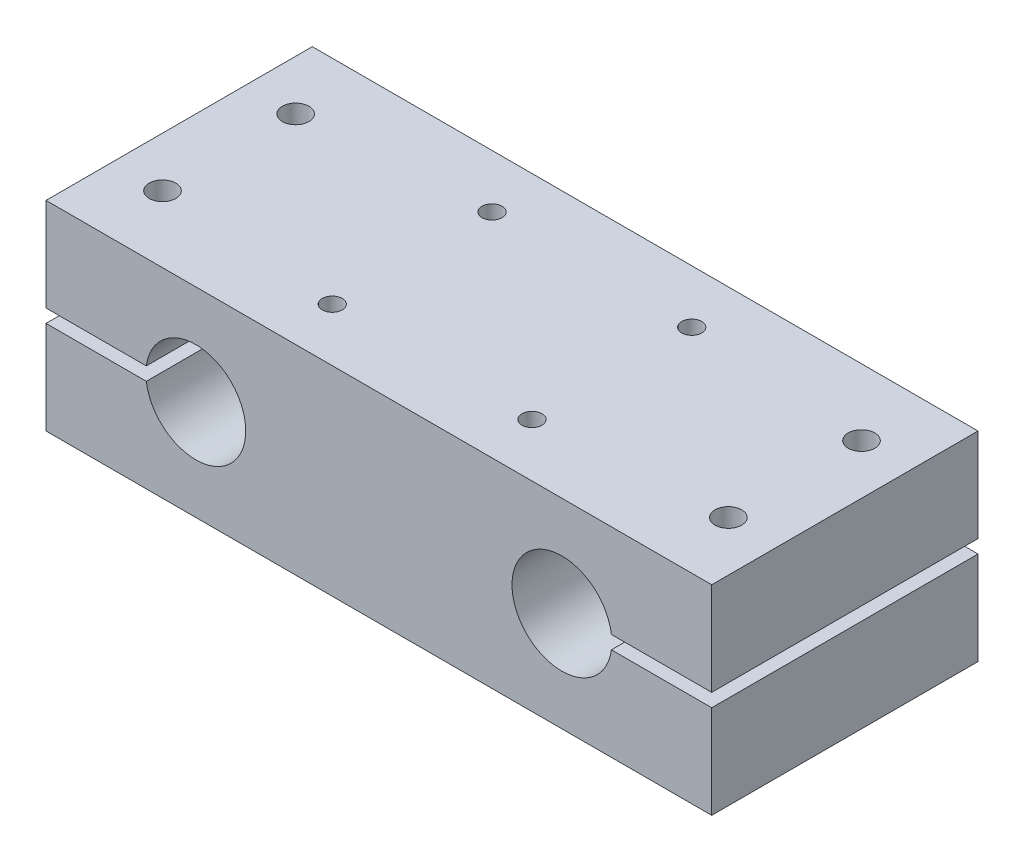
SolidWorks part; units mm, degrees
material "Сосна"
ref_plane "Спереди" through (0, 0, 0) normal (0, 0, 1) x (1, 0, 0)
ref_plane "Сверху" through (0, 0, 0) normal (0, 1, 0) x (1, 0, 0)
ref_plane "Справа" through (0, 0, 0) normal (1, 0, 0) x (0, 0, -1)
sketch "Эскиз1" plane through (0, 0, 0) normal (0, 0, 1) x (1, 0, 0)
  line L1 (0, 0) -> (100, 0)
  line L2 (0, 0) -> (0, 14)
  line L3 (0, 30) -> (100, 30)
  line L4 (100, 0) -> (100, 14)
  line L6 (0, 16) -> (15.067, 16)
  line L8 (0, 14) -> (15.067, 14)
  line L9 (0, 16) -> (0, 30)
  line L10 (100, 16) -> (84.933, 16)
  line L11 (100, 14) -> (84.933, 14)
  line L12 (100, 16) -> (100, 30)
  arc A0 (15.067, 14) -> (15.067, 16) centre (22.5, 15) ccw
  arc A1 (84.933, 16) -> (84.933, 14) centre (77.5, 15) ccw
  dimension "D1" = 100
  dimension "D2" = 30
extrude "Бобышка-Вытянуть1" add sketch "Эскиз1" along normal blind 40
sketch "Эскиз2" plane through (0, 0, 0) normal (0, -1, 0) x (1, 0, 0)
  line L0 (50, 40) -> (50, 0) construction
  line L1 (0, 0) -> (100, 0) construction
  line L2 (100, 0) -> (92.5, 0)
  line L3 (7.5, 0) -> (7.5, 40) construction
  line L4 (0, 40) -> (100, 40) construction
  line L5 (92.5, 0) -> (92.5, 40) construction
  line L6 (50, 20) -> (50, 8) construction
  circle A0 centre (7.5, 30) radius 2
  circle A1 centre (7.5, 10) radius 2
  circle A2 centre (92.5, 30) radius 2
  circle A3 centre (92.5, 10) radius 2
  circle A4 centre (35, 32) radius 1.5
  circle A5 centre (65, 32) radius 1.5
  circle A6 centre (35, 8) radius 1.5
  circle A7 centre (65, 8) radius 1.5
  dimension "D5" = 4
  dimension "D6" = 4
  dimension "D7" = 4
  dimension "D2" = 7.5
  dimension "D3" = 10
  dimension "D4" = 10
extrude "Вырез-Вытянуть1" cut sketch "Эскиз2" against normal through all contours A0 | A1 | A3 | A2 | A4 | A6 | A7 | A5
